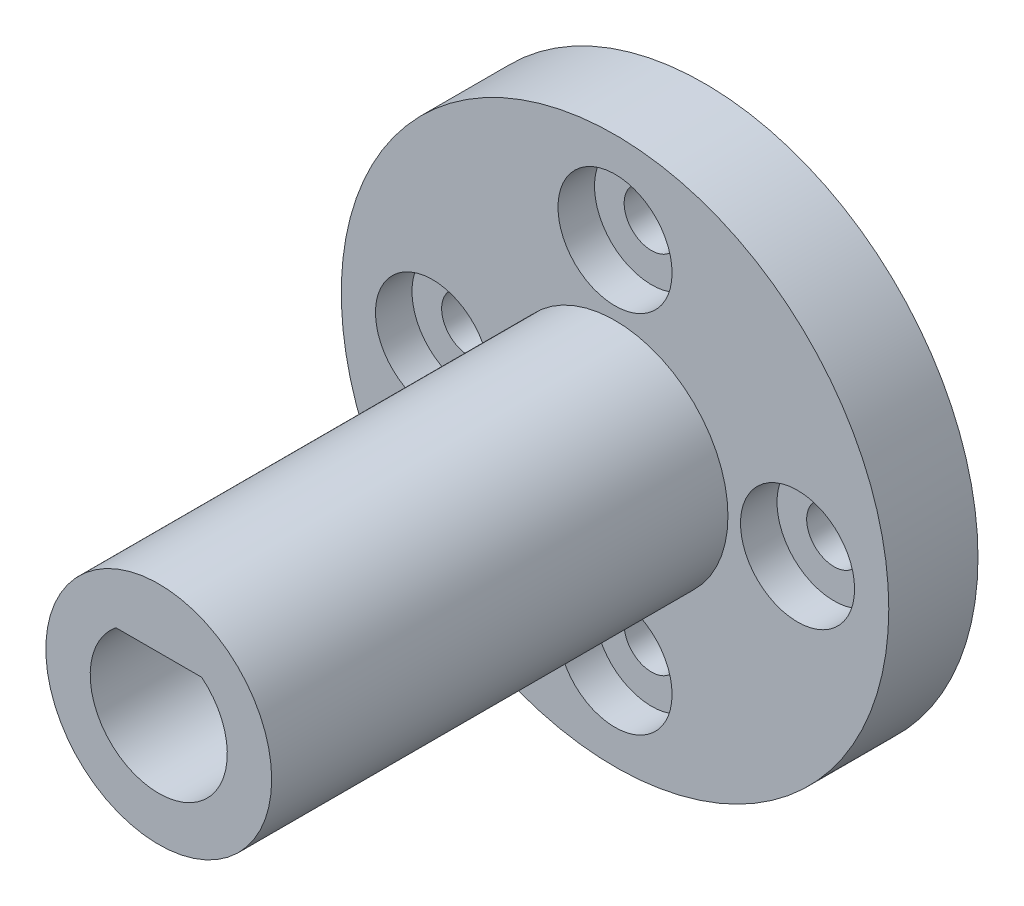
SolidWorks part; units mm, degrees
ref_plane "Plan de face" through (0, 0, 0) normal (0, 0, 1) x (1, 0, 0)
ref_plane "Plan de dessus" through (0, 0, 0) normal (0, 1, 0) x (1, 0, 0)
ref_plane "Plan de droite" through (0, 0, 0) normal (1, 0, 0) x (0, 0, -1)
sketch "Esquisse1" plane through (0, 0, 0) normal (0, 0, 1) x (1, 0, 0)
  circle A0 centre (0, 0) radius 12
  dimension "D1" = 24
extrude "Boss.-Extru.1" add sketch "Esquisse1" along normal blind 3.91
sketch "Esquisse6" plane through (0, 0, 0) normal (0, 0, -1) x (-1, 0, 0)
  circle A0 centre (0, 0) radius 4
  dimension "D1" = 8
extrude "Enlèv. mat.-Extru.2" cut sketch "Esquisse6" against normal blind 1.91
sketch "Esquisse7" plane through (0, 0, 3.91) normal (0, 0, 1) x (1, 0, 0)
  line L0 (1.8791, 2.345) -> (-1.8791, 2.345)
  line L1 (-5.4714, -3.005) -> (6.192, -3.005) construction
  arc A0 (-1.8791, 2.345) -> (1.8791, 2.345) centre (0, 0) ccw
  circle A1 centre (0, 0) radius 4.95
  dimension "D1" = 6.01
  dimension "D3" = 9.9
  dimension "D2" = 5.35
extrude "Boss.-Extru.2" add sketch "Esquisse7" along normal blind 20 contours A1 L1 A0 L0 | L1 A1
hole_wizard "Chambrage pour vis à tête ronde bombée M21" positions "Esquisse10" profile "Esquisse11" counterbore size "M2" standard "Ansi Metric" end condition through all
sketch "Esquisse10" plane through (0, 0, 3.91) normal (0, 0, 1) x (1, 0, 0)
  point P0 (0, 8)
  dimension "D1" = 8
sketch "Esquisse11" plane through (0, 8, 3.91) normal (1, 0, 0) x (0, -1, 0)
  line L0 (0, 0) -> (0, 3.91)
  line L1 (0, 3.91) -> (1.2, 3.91)
  line L3 (1.2, 3.91) -> (1.2, 1.6)
  line L4 (1.2, 1.6) -> (2.5, 1.6)
  line L5 (2.5, 1.6) -> (2.5, 0)
  line L7 (2.5, 0) -> (0, 0)
  line L11 (0, -6.35) -> (0, 107.95) construction
  dimension "Diamètre du perçage jusqu'au prochain" = 2.4
  dimension "Profondeur du perçage jusqu'au prochain" = 3.91
  dimension "Diamètre du chambrage" = 5
  dimension "Profondeur du chambrage" = 1.6
pattern_circular "Répétition circulaire2" count 4 every 90 about axis through (0, 0, 0) along (0, 0, 1) of "Chambrage pour vis à tête ronde bombée M21"
